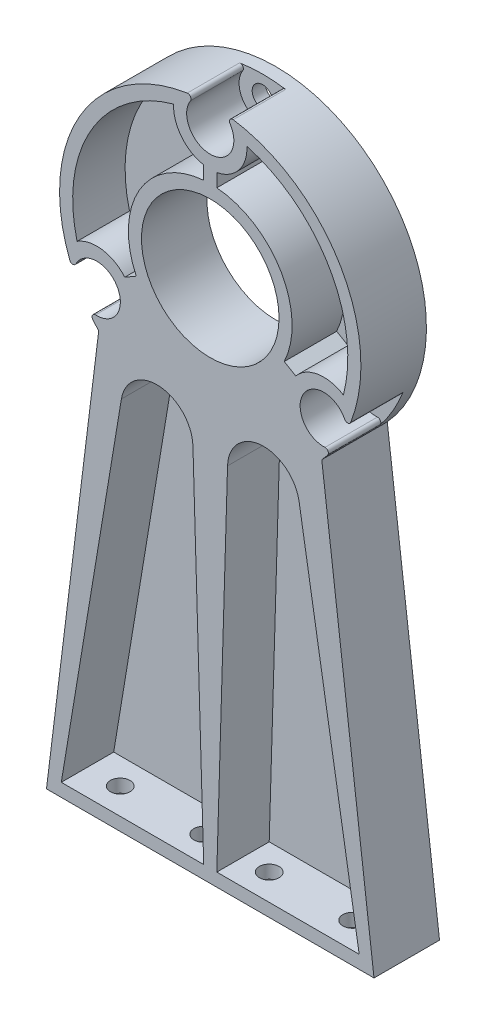
SolidWorks part; units mm, degrees
ref_plane "前视基准面" through (0, 0, 0) normal (0, 0, 1) x (1, 0, 0)
ref_plane "上视基准面" through (0, 0, 0) normal (0, 1, 0) x (1, 0, 0)
ref_plane "右视基准面" through (0, 0, 0) normal (1, 0, 0) x (0, 0, -1)
sketch "草图1" plane through (0, 0, 0) normal (0, 0, 1) x (1, 0, 0)
  line L0 (-25, 0) -> (25, 0)
  line L1 (-25, 0) -> (-14.8868, 81.8396)
  line L2 (25, 0) -> (14.8868, 81.8396)
  circle A0 centre (0, 80) radius 10.5
  arc A1 (14.8868, 81.8396) -> (-14.8868, 81.8396) centre (0, 80) ccw
  point P4 (0, 0)
  dimension "D2" = 21
  dimension "D3" = 30
  dimension "D1" = 50
  dimension "D4" = 80
extrude "凸台-拉伸1" add sketch "草图1" along normal blind 10
sketch "草图2" plane through (0, 0, 10) normal (0, 0, 1) x (1, 0, 0)
  line L0 (-13.565, 57.2626) -> (-22.7376, 2)
  line L1 (-2.6417, 56.5276) -> (-1, 2)
  line L2 (2.6417, 56.5276) -> (1, 2)
  line L3 (13.565, 57.2626) -> (22.7376, 2)
  line L4 (1, 2) -> (22.7376, 2)
  line L11 (-6.3486, 61.5624) -> (-8.1392, 56.362) construction
  line L13 (22.7376, 2) -> (12.9019, 81.5943)
  line L14 (-22.7376, 2) -> (22.7376, 2)
  line L15 (-12.9019, 81.5943) -> (-22.7376, 2)
  line L17 (-22.7376, 2) -> (-1, 2)
  line L24 (6.3486, 61.5624) -> (8.1392, 56.362) construction
  arc A7 (-15.5208, 60.4014) -> (13.111, 58.7138) centre (0, 80) ccw construction
  arc A10 (-2.6417, 56.5276) -> (-13.565, 57.2626) centre (-8.1392, 56.362) ccw
  arc A11 (13.565, 57.2626) -> (2.6417, 56.5276) centre (8.1392, 56.362) ccw
  point P0 (0, 38.9049)
  dimension "D6" = 50
  dimension "D7" = 11
  dimension "D8" = 11
  dimension "D2" = 2
extrude "切除-拉伸2" cut sketch "草图2" against normal blind 8
sketch "草图3" plane through (0, 2, 0) normal (0, 1, 0) x (1, 0, 0)
  line L0 (-1, -2) -> (-1, -10) construction
  line L2 (-22.7376, -2) -> (-1, -2) construction
  line L4 (1, -2) -> (22.7376, -2) construction
  line L5 (1, -2) -> (1, -10) construction
  circle A0 centre (-17.74, -6) radius 1.5
  circle A1 centre (-5, -6) radius 1.5
  circle A2 centre (5, -6) radius 1.5
  circle A3 centre (17.74, -6) radius 1.5
  dimension "D1" = 4
  dimension "D2" = 12.74
  dimension "D5" = 3
  dimension "D6" = 3
  dimension "D11" = 3
  dimension "D12" = 3
  dimension "D3" = 4
  dimension "D4" = 4
  dimension "D7" = 12.74
  dimension "D8" = 4
  dimension "D9" = 4
  dimension "D10" = 4
extrude "切除-拉伸3" cut sketch "草图3" against normal through all
sketch "草图4" plane through (0, 0, 10) normal (0, 0, 1) x (1, 0, 0)
  line L0 (0, 80) -> (0, 100) construction
  line L1 (0, 80) -> (17.3205, 70) construction
  line L2 (0, 80) -> (-17.3205, 70) construction
  line L3 (25, 0) -> (14.8868, 81.8396) construction
  line L4 (-14.8868, 81.8396) -> (-25, 0) construction
  line L5 (17.0251, 64.5356) -> (14.8868, 81.8396)
  line L6 (-14.8868, 81.8396) -> (-17.0251, 64.5356)
  circle A0 centre (0, 80) radius 20 construction
  circle A1 centre (0, 100) radius 1.6
  arc A2 (16.5211, 68.614) -> (16.2078, 71.1497) centre (17.3205, 70) ccw
  arc A3 (-16.2078, 71.1497) -> (-16.5211, 68.614) centre (-17.3205, 70) ccw
  arc A4 (17.0251, 64.5356) -> (-17.0251, 64.5356) centre (0, 80) ccw
  arc A5 (14.8868, 81.8396) -> (-14.8868, 81.8396) centre (0, 80) ccw construction
  arc A6 (14.8868, 81.8396) -> (-14.8868, 81.8396) centre (0, 80) ccw
  line M12 (25, 0) -> (14.8868, 81.8396)
  arc M13 (14.8868, 81.8396) -> (-14.8868, 81.8396) centre (0, 80) ccw
  line M14 (-14.8868, 81.8396) -> (-25, 0)
  dimension "D1" = 40
  dimension "D4" = 3
  dimension "D5" = 3.2
  dimension "D6" = 3.2
  dimension "D7" = 3.2
  dimension "D2" = 120
  dimension "D3" = 120
extrude "凸台-拉伸3" add sketch "草图4" against normal blind 10 contours A4 A3 A2 A1 M12 M14 M13
sketch "草图5" plane through (0, 0, 10) normal (0, 0, 1) x (1, 0, 0)
  circle A0 centre (-17.3205, 70) radius 1.6
  circle A1 centre (17.3205, 70) radius 1.6
extrude "切除-拉伸4" cut sketch "草图5" against normal blind 10
sketch "草图6" plane through (0, 0, 10) normal (0, 0, 1) x (1, 0, 0)
  line L1 (11.2906, 74.6361) -> (13.0487, 73.621)
  line L9 (1, 92.4599) -> (1, 94.49)
  line L11 (-1, 92.4599) -> (-1, 94.49)
  line L18 (-11.2906, 74.6361) -> (-13.0487, 73.621)
  circle A0 centre (0, 100) radius 5.6 construction
  arc A1 (-5.5948, 100.241) -> (-20.3266, 74.7247) centre (0, 80) ccw
  arc A2 (1, 94.49) -> (5.5948, 100.241) centre (0, 100) ccw
  circle A3 centre (17.3205, 70) radius 5.6 construction
  arc A4 (11.2906, 74.6361) -> (1, 92.4599) centre (0, 80) ccw
  arc A5 (20.3266, 74.7247) -> (5.5948, 100.241) centre (0, 80) ccw
  circle A6 centre (-17.3205, 70) radius 5.6 construction
  circle A8 centre (0, 80) radius 12.5
  arc A9 (-1, 92.4599) -> (-11.2906, 74.6361) centre (0, 80) ccw
  circle A17 centre (-17.3205, 70) radius 3.6
  circle A18 centre (-17.3205, 70) radius 3.6
  circle A20 centre (17.3205, 70) radius 3.6
  circle A21 centre (17.3205, 70) radius 3.6
  arc A22 (-5.5948, 100.241) -> (-1, 94.49) centre (0, 100) ccw
  circle A23 centre (0, 100) radius 3.6
  circle A24 centre (0, 100) radius 3.6
  arc A25 (-13.0487, 73.621) -> (-20.3266, 74.7247) centre (-17.3205, 70) ccw
  arc A26 (20.3266, 74.7247) -> (13.0487, 73.621) centre (17.3205, 70) ccw
  dimension "D1" = 2
  dimension "D3" = 2
  dimension "D4" = 2
  dimension "D5" = 2
  dimension "D6" = 2
  dimension "D7" = 2
  dimension "D8" = 2
extrude "切除-拉伸5" cut sketch "草图6" against normal blind 8
fillet "圆角1" radius 0.5 6 edges at (20.8987, 70.3956, 6) (18.767, 66.7034, 6) (-18.767, 66.7034, 6) (-20.8987, 70.3956, 6) (-2.1317, 102.901, 6) (2.1317, 102.901, 6)
